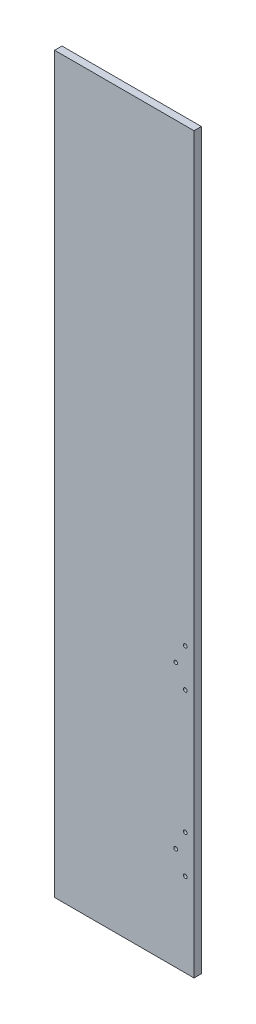
SolidWorks part; units mm, degrees
ref_plane "Front Plane" through (0, 0, 0) normal (0, 0, 1) x (1, 0, 0)
ref_plane "Top Plane" through (0, 0, 0) normal (0, 1, 0) x (1, 0, 0)
ref_plane "Right Plane" through (0, 0, 0) normal (1, 0, 0) x (0, 0, -1)
sketch "Sketch1" plane through (0, 0, 0) normal (0, 0, 1) x (1, 0, 0)
  line L1 (95, -500) -> (-95, -500)
  line L2 (95, -500) -> (95, 500)
  line L3 (95, 500) -> (-95, 500)
  line L4 (-95, -500) -> (-95, 500)
  line L5 (95, -500) -> (-95, 500) construction
  line L6 (95, 500) -> (-95, -500) construction
  point P0 (0, 0)
  dimension "D1" = 190
  dimension "D2" = 1000
extrude "Boss-Extrude1" add sketch "Sketch1" along normal blind 10
sketch "Sketch2" plane through (0, 0, 10) normal (0, 0, 1) x (1, 0, 0)
  line L0 (-95, -500) -> (95, -500) construction
  line L1 (95, -500) -> (95, 500) construction
  circle A0 centre (83, -386) radius 2.5
  circle A1 centre (70, -360) radius 2.5
  circle A2 centre (83, -334) radius 2.5
  circle A3 centre (83, -166) radius 2.5
  circle A4 centre (70, -140) radius 2.5
  circle A5 centre (83, -114) radius 2.5
  dimension "D1" = 114
  dimension "D2" = 12
  dimension "D3" = 140
  dimension "D4" = 25
  dimension "D5" = 12
  dimension "D6" = 166
  dimension "D7" = 12
  dimension "D8" = 334
  dimension "D9" = 25
  dimension "D10" = 360
  dimension "D11" = 12
  dimension "D12" = 386
extrude "Cut-Extrude1" cut sketch "Sketch2" against normal through all
